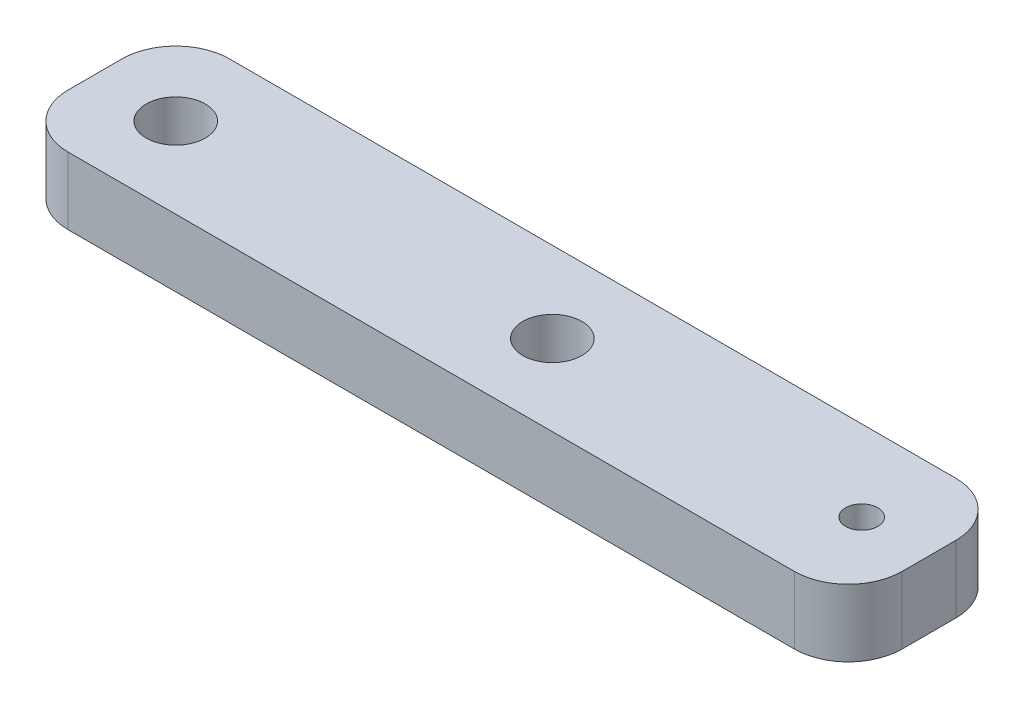
SolidWorks part; units mm, degrees
ref_plane "前视基准面" through (0, 0, 0) normal (0, 0, 1) x (1, 0, 0)
ref_plane "上视基准面" through (0, 0, 0) normal (0, 1, 0) x (1, 0, 0)
ref_plane "右视基准面" through (0, 0, 0) normal (1, 0, 0) x (0, 0, -1)
sketch "草图1" plane through (0, 0, 0) normal (0, 1, 0) x (1, 0, 0)
  line L1 (0, 0.3585) -> (31, 0.3585)
  line L2 (0, 0.3585) -> (0, -5.6415)
  line L3 (0, -5.6415) -> (31, -5.6415)
  line L4 (31, 0.3585) -> (31, -5.6415)
  dimension "D1" = 6
  dimension "D2" = 31
extrude "凸台-拉伸1" add sketch "草图1" along normal blind 2.5
sketch "草图2" plane through (0, 2.5, 0) normal (0, 1, 0) x (1, 0, 0)
  line L0 (0, 0.3585) -> (0, -5.6415) construction
  circle A0 centre (3, -2.6415) radius 1.1
  circle A1 centre (17, -2.6415) radius 1.1
  dimension "D1" = 14
  dimension "D2" = 2.2
  dimension "D3" = 2.2
  dimension "D4" = 3
extrude "切除-拉伸1" cut sketch "草图2" against normal through all
sketch "草图3" plane through (0, 2.5, 0) normal (0, 1, 0) x (1, 0, 0)
  line L0 (31, -5.6415) -> (31, 0.3585) construction
  circle A0 centre (28.5, -2.6415) radius 0.6
  dimension "D1" = 1.2
  dimension "D2" = 2.5
extrude "切除-拉伸2" cut sketch "草图3" against normal through all
fillet "圆角1" radius 2 4 edges at (0, 1.25, -0.3585) (31, 1.25, -0.3585) (31, 1.25, 5.6415) (0, 1.25, 5.6415)
